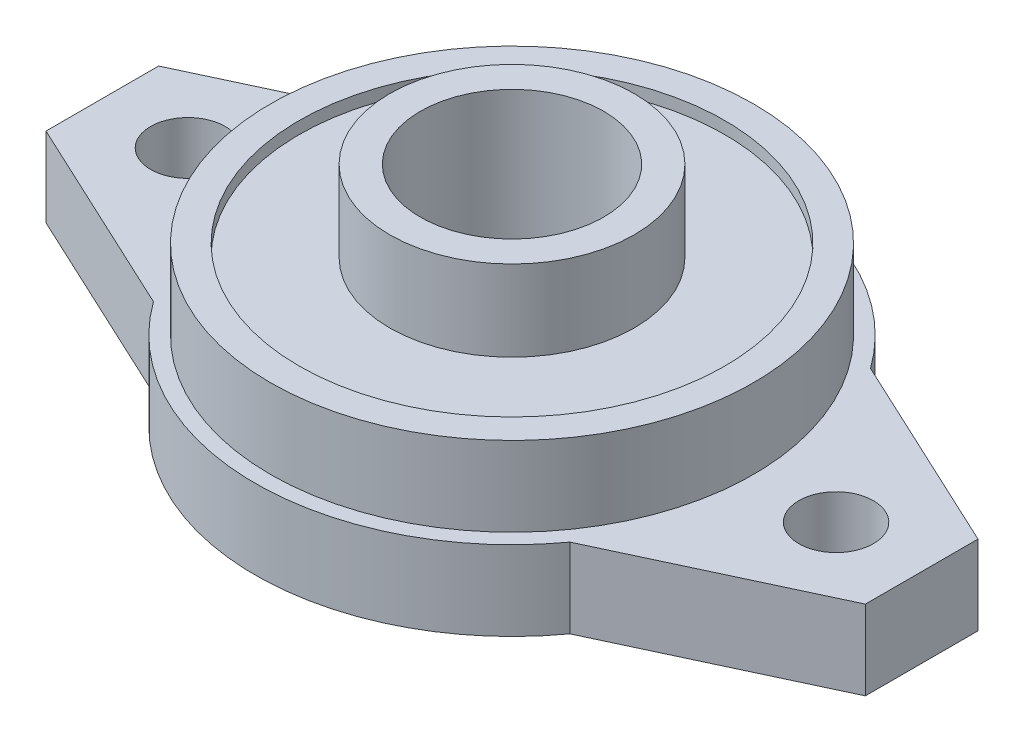
SolidWorks part; units mm, degrees
material "锌 AC41A 合金，作为铸件"
ref_plane "前视基准面" through (0, 0, 0) normal (0, 0, 1) x (1, 0, 0)
ref_plane "上视基准面" through (0, 0, 0) normal (0, 1, 0) x (1, 0, 0)
ref_plane "右视基准面" through (0, 0, 0) normal (1, 0, 0) x (0, 0, -1)
sketch "草图1" plane through (0, 0, 0) normal (0, 1, 0) x (1, 0, 0)
  line L0 (-643.3584, 0) -> (31524.5638, 0) construction
  line L1 (0, -643.3584) -> (0, 31524.5638) construction
  line L2 (-33.5, 4.605) -> (-33.5, -4.605)
  line L3 (-33.5, 4.605) -> (-17.0257, 12.2932)
  line L4 (-33.5, -4.605) -> (-17.0257, -12.2932)
  line L5 (33.5, -4.605) -> (17.0257, -12.2932)
  line L6 (33.5, 4.605) -> (17.0257, 12.2932)
  line L7 (33.5, 4.605) -> (33.5, -4.605)
  circle A0 centre (0, 0) radius 7.5
  circle A1 centre (0, 0) radius 21
  circle A2 centre (-26.5, 0) radius 3.05
  circle A3 centre (26.5, 0) radius 3.05
  point P13 (-33.5, 0)
  point P21 (33.5, 0)
  dimension "D1" = 6.1
  dimension "D2" = 42
  dimension "D3" = 15
  dimension "D4" = 33.5
  dimension "D5" = 26.5
extrude "凸台-拉伸1" add sketch "草图1" along normal blind 6.5 contours A1 L3 L2 L4 A2 | A1 A0 | A1 L5 L7 L6 A3
sketch "草图2" plane through (0, 6.5, 0) normal (0, 1, 0) x (1, 0, 0)
  circle A0 centre (0, 0) radius 19.75
  circle A1 centre (0, 0) radius 7.5 construction
  circle A2 centre (0, 0) radius 7.5
  dimension "D1" = 39.5
extrude "凸台-拉伸2" add sketch "草图2" along normal blind 6.5
sketch "草图3" plane through (0, 13, 0) normal (0, 1, 0) x (1, 0, 0)
  circle A0 centre (0, 0) radius 10
  circle A1 centre (0, 0) radius 7.5 construction
  circle A2 centre (0, 0) radius 7.5
  dimension "D1" = 20
extrude "凸台-拉伸3" add sketch "草图3" along normal blind 5.6
sketch "草图4" plane through (0, 13, 0) normal (0, 1, 0) x (1, 0, 0)
  circle A0 centre (0, 0) radius 10 construction
  circle A1 centre (0, 0) radius 10
  circle A2 centre (0, 0) radius 17.4
  circle A3 centre (0, 0) radius 19.75 construction
  dimension "D1" = 2.35
extrude "切除-拉伸1" cut sketch "草图4" against normal blind 1
